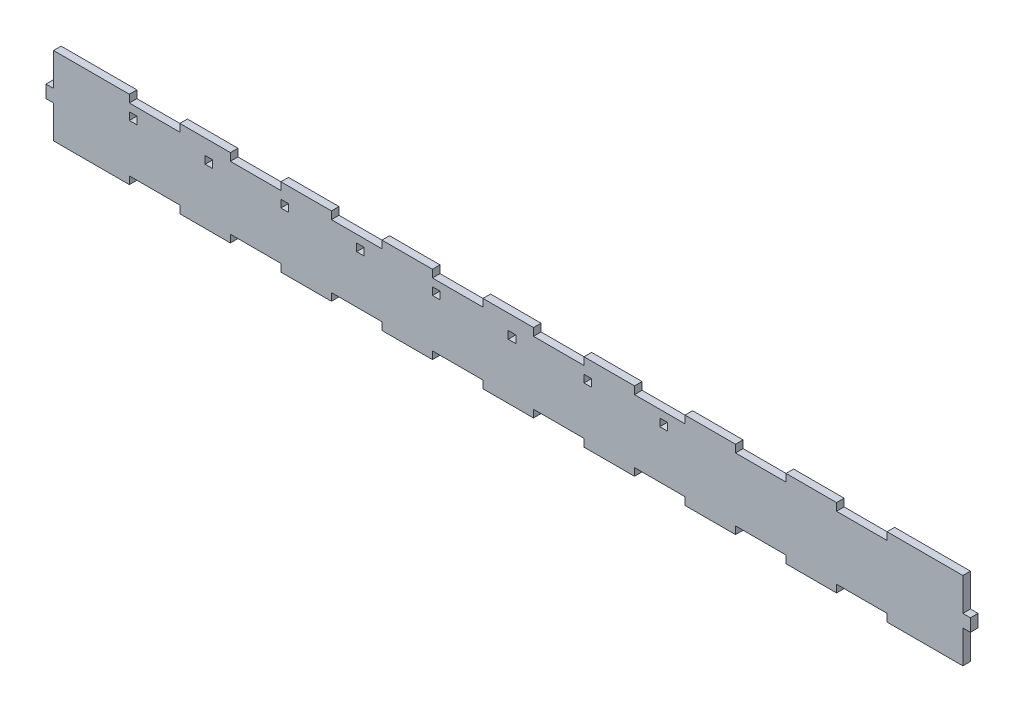
SolidWorks part; units mm, degrees
ref_plane "Front Plane" through (0, 0, 0) normal (0, 0, 1) x (1, 0, 0)
ref_plane "Top Plane" through (0, 0, 0) normal (0, 1, 0) x (1, 0, 0)
ref_plane "Right Plane" through (0, 0, 0) normal (1, 0, 0) x (0, 0, -1)
sketch "Эскиз1" plane through (0, 0, 0) normal (0, 0, 1) x (1, 0, 0)
  line L0 (193.8008, 182.8751) -> (201.5139, 182.8751)
  line L1 (201.5139, 182.8751) -> (201.5139, 187.2691)
  line L2 (201.5139, 187.2691) -> (225.208, 187.2691)
  line L3 (225.208, 187.2691) -> (225.208, 182.8751)
  line L4 (225.208, 182.8751) -> (247.3733, 182.8751)
  line L5 (247.3733, 182.8751) -> (247.3733, 187.2691)
  line L6 (247.3733, 187.2691) -> (271.0674, 187.2691)
  line L7 (271.0674, 187.2691) -> (271.0674, 182.8751)
  line L8 (271.0674, 182.8751) -> (301.6403, 182.8751)
  line L9 (301.6403, 182.8751) -> (301.6403, 159.44)
  line L10 (301.6403, 159.44) -> (307.3727, 159.44)
  line L11 (307.3727, 159.44) -> (307.3727, 141.2778)
  line L12 (307.3727, 141.2778) -> (301.6403, 141.2778)
  line L13 (301.6403, 141.2778) -> (301.6403, 124.2873)
  line L14 (301.6403, 124.2873) -> (307.3727, 124.2873)
  line L15 (307.3727, 124.2873) -> (307.3727, 106.1251)
  line L16 (307.3727, 106.1251) -> (301.6403, 106.1251)
  line L17 (301.6403, 106.1251) -> (301.6403, 89.1347)
  line L18 (301.6403, 89.1347) -> (307.3727, 89.1347)
  line L19 (307.3727, 89.1347) -> (307.3727, 70.9725)
  line L20 (307.3727, 70.9725) -> (301.6403, 70.9725)
  line L21 (301.6403, 70.9725) -> (301.6403, 53.9821)
  line L22 (301.6403, 53.9821) -> (307.3727, 53.9821)
  line L23 (307.3727, 53.9821) -> (307.3727, 35.8199)
  line L24 (307.3727, 35.8199) -> (301.6403, 35.8199)
  line L25 (301.6403, 35.8199) -> (301.6403, 18.8294)
  line L26 (301.6403, 18.8294) -> (307.3727, 18.8294)
  line L27 (307.3727, 18.8294) -> (307.3727, 0.6672)
  line L28 (307.3727, 0.6672) -> (301.6403, 0.6672)
  line L29 (301.6403, 0.6672) -> (301.6403, -16.3232)
  line L30 (301.6403, -16.3232) -> (307.3727, -16.3232)
  line L31 (307.3727, -16.3232) -> (307.3727, -34.4854)
  line L32 (307.3727, -34.4854) -> (301.6403, -34.4854)
  line L33 (301.6403, -67.207) -> (270.4792, -67.207)
  line L34 (270.4792, -67.207) -> (270.4792, -71.6011)
  line L35 (270.4792, -71.6011) -> (246.7851, -71.6011)
  line L36 (246.7851, -71.6011) -> (246.7851, -67.207)
  line L37 (246.7851, -67.207) -> (224.6198, -67.207)
  line L38 (224.6198, -67.207) -> (224.6198, -71.6011)
  line L39 (224.6198, -71.6011) -> (200.9257, -71.6011)
  line L40 (200.9257, -71.6011) -> (200.9257, -67.207)
  line L41 (200.9257, -67.207) -> (193.2126, -67.207)
  line L42 (193.2126, -67.207) -> (178.7604, -67.207)
  line L43 (178.7604, -67.207) -> (178.7604, -71.6011)
  line L44 (178.7604, -71.6011) -> (155.0663, -71.6011)
  line L45 (155.0663, -71.6011) -> (155.0663, -67.207)
  line L46 (155.0663, -67.207) -> (132.901, -67.207)
  line L47 (132.901, -67.207) -> (132.901, -71.6011)
  line L48 (132.901, -71.6011) -> (109.2069, -71.6011)
  line L49 (109.2069, -71.6011) -> (109.2069, -67.207)
  line L50 (109.2069, -67.207) -> (87.0415, -67.207)
  line L51 (87.0415, -67.207) -> (87.0415, -71.6011)
  line L52 (87.0415, -71.6011) -> (63.3475, -71.6011)
  line L53 (63.3475, -71.6011) -> (63.3475, -67.207)
  line L54 (63.3475, -67.207) -> (41.1821, -67.207)
  line L55 (41.1821, -67.207) -> (41.1821, -71.6011)
  line L56 (41.1821, -71.6011) -> (17.4881, -71.6011)
  line L57 (17.4881, -71.6011) -> (17.4881, -67.207)
  line L58 (17.4881, -67.207) -> (-4.6773, -67.207)
  line L59 (-4.6773, -67.207) -> (-4.6773, -71.6011)
  line L60 (-4.6773, -71.6011) -> (-28.3713, -71.6011)
  line L61 (-28.3713, -71.6011) -> (-28.3713, -67.207)
  line L62 (-28.3713, -67.207) -> (-58.356, -67.207)
  line L63 (-58.356, -67.207) -> (-58.356, -34.4854)
  line L64 (-58.356, -34.4854) -> (-64.0885, -34.4854)
  line L65 (-64.0885, -34.4854) -> (-64.0885, -16.3232)
  line L66 (-64.0885, -16.3232) -> (-58.356, -16.3232)
  line L67 (-58.356, -16.3232) -> (-58.356, 0.6672)
  line L68 (-58.356, 0.6672) -> (-64.0885, 0.6672)
  line L69 (-64.0885, 0.6672) -> (-64.0885, 18.8294)
  line L70 (-64.0885, 18.8294) -> (-58.356, 18.8294)
  line L71 (-58.356, 18.8294) -> (-58.356, 35.8199)
  line L72 (-58.356, 35.8199) -> (-64.0885, 35.8199)
  line L73 (-64.0885, 35.8199) -> (-64.0885, 53.9821)
  line L74 (-64.0885, 53.9821) -> (-58.356, 53.9821)
  line L75 (-58.356, 53.9821) -> (-58.356, 70.9725)
  line L76 (-58.356, 70.9725) -> (-64.0885, 70.9725)
  line L77 (-64.0885, 70.9725) -> (-64.0885, 89.1347)
  line L78 (-64.0885, 89.1347) -> (-58.356, 89.1347)
  line L79 (-58.356, 89.1347) -> (-58.356, 106.1251)
  line L80 (-58.356, 106.1251) -> (-64.0885, 106.1251)
  line L81 (-64.0885, 106.1251) -> (-64.0885, 124.2873)
  line L82 (-64.0885, 124.2873) -> (-58.356, 124.2873)
  line L83 (-58.356, 124.2873) -> (-58.356, 141.2778)
  line L84 (-58.356, 141.2778) -> (-64.0885, 141.2778)
  line L85 (-64.0885, 141.2778) -> (-64.0885, 159.44)
  line L86 (-64.0885, 159.44) -> (-58.356, 159.44)
  line L87 (-58.356, 159.44) -> (-58.356, 182.8751)
  line L88 (-58.356, 182.8751) -> (-27.7831, 182.8751)
  line L89 (-27.7831, 182.8751) -> (-27.7831, 187.2691)
  line L90 (-27.7831, 187.2691) -> (-4.0891, 187.2691)
  line L91 (-4.0891, 187.2691) -> (-4.0891, 182.8751)
  line L92 (-4.0891, 182.8751) -> (18.0763, 182.8751)
  line L93 (18.0763, 182.8751) -> (18.0763, 187.2691)
  line L94 (18.0763, 187.2691) -> (41.7703, 187.2691)
  line L95 (41.7703, 187.2691) -> (41.7703, 182.8751)
  line L96 (41.7703, 182.8751) -> (63.9357, 182.8751)
  line L97 (63.9357, 182.8751) -> (63.9357, 187.2691)
  line L98 (63.9357, 187.2691) -> (87.6297, 187.2691)
  line L99 (87.6297, 187.2691) -> (87.6297, 182.8751)
  line L100 (87.6297, 182.8751) -> (109.7951, 182.8751)
  line L101 (109.7951, 182.8751) -> (109.7951, 187.2691)
  line L102 (109.7951, 187.2691) -> (133.4892, 187.2691)
  line L103 (133.4892, 187.2691) -> (133.4892, 182.8751)
  line L104 (133.4892, 182.8751) -> (155.6545, 182.8751)
  line L105 (155.6545, 182.8751) -> (155.6545, 187.2691)
  line L106 (155.6545, 187.2691) -> (179.3486, 187.2691)
  line L107 (179.3486, 187.2691) -> (179.3486, 182.8751)
  line L108 (179.3486, 182.8751) -> (193.8008, 182.8751)
  line L109 (-61.3459, -78.4574) -> (-30.9012, -78.4574)
  line L110 (-30.9012, -78.4574) -> (-30.9012, -82.7686)
  line L111 (-30.9012, -82.7686) -> (-6.4981, -82.7686)
  line L112 (-6.4981, -82.7686) -> (-6.4981, -78.4574)
  line L113 (-6.4981, -78.4574) -> (14.958, -78.4574)
  line L114 (14.958, -78.4574) -> (14.958, -82.7686)
  line L115 (14.958, -82.7686) -> (39.3435, -82.7686)
  line L116 (39.3435, -82.7686) -> (39.3435, -78.4574)
  line L117 (39.3435, -78.4574) -> (60.7425, -78.4574)
  line L118 (60.7425, -78.4574) -> (60.7425, -82.7686)
  line L119 (60.7425, -82.7686) -> (85.2373, -82.7686)
  line L120 (85.2373, -82.7686) -> (85.2373, -78.4574)
  line L121 (85.2373, -78.4574) -> (106.671, -78.4574)
  line L122 (106.671, -78.4574) -> (106.671, -82.7686)
  line L123 (106.671, -82.7686) -> (131.0375, -82.7686)
  line L124 (131.0375, -82.7686) -> (131.0375, -78.4574)
  line L125 (131.0375, -78.4574) -> (152.4105, -78.4574)
  line L126 (152.4105, -78.4574) -> (152.4105, -82.7686)
  line L127 (152.4105, -82.7686) -> (176.9033, -82.7686)
  line L128 (176.9033, -82.7686) -> (176.9033, -78.4574)
  line L129 (176.9033, -78.4574) -> (198.3512, -78.4574)
  line L130 (198.3512, -78.4574) -> (198.3512, -82.7686)
  line L131 (198.3512, -82.7686) -> (222.7186, -82.7686)
  line L132 (222.7186, -82.7686) -> (222.7186, -78.4574)
  line L133 (222.7186, -78.4574) -> (244.191, -78.4574)
  line L134 (244.191, -78.4574) -> (244.191, -82.7686)
  line L135 (244.191, -82.7686) -> (268.7496, -82.7686)
  line L136 (268.7496, -82.7686) -> (268.7496, -78.4574)
  line L137 (268.7496, -78.4574) -> (299.0743, -78.4574)
  line L138 (299.0743, -78.4574) -> (299.0743, -90.1442)
  line L139 (299.0743, -90.1442) -> (307.1171, -90.1442)
  line L140 (307.1171, -90.1442) -> (307.1106, -97.0135)
  line L141 (307.1106, -97.0135) -> (299.0743, -97.0135)
  line L142 (299.0743, -97.0135) -> (299.0743, -109.9393)
  line L143 (299.0743, -109.9393) -> (268.7496, -109.9393)
  line L144 (268.7496, -109.9393) -> (268.7496, -106.2126)
  line L145 (268.7496, -106.2126) -> (244.191, -106.2126)
  line L146 (244.191, -106.2126) -> (244.191, -109.9393)
  line L147 (244.191, -109.9393) -> (222.7186, -109.9393)
  line L148 (222.7186, -109.9393) -> (222.7186, -106.2126)
  line L149 (222.7186, -106.2126) -> (198.3512, -106.2126)
  line L150 (198.3512, -106.2126) -> (198.3512, -109.9393)
  line L151 (198.3512, -109.9393) -> (176.9033, -109.9393)
  line L152 (176.9033, -109.9393) -> (176.9033, -106.2126)
  line L153 (176.9033, -106.2126) -> (152.4105, -106.2126)
  line L154 (152.4105, -106.2126) -> (152.4105, -109.9393)
  line L155 (152.4105, -109.9393) -> (131.0375, -109.9393)
  line L156 (131.0375, -109.9393) -> (131.0369, -106.2126)
  line L157 (131.0369, -106.2126) -> (106.671, -106.2126)
  line L158 (106.671, -106.2126) -> (106.671, -109.9393)
  line L159 (106.671, -109.9393) -> (85.2373, -109.9393)
  line L160 (85.2373, -109.9393) -> (85.2373, -106.2126)
  line L161 (85.2373, -106.2126) -> (60.7425, -106.2126)
  line L162 (60.7425, -106.2126) -> (60.7425, -109.9393)
  line L163 (60.7425, -109.9393) -> (39.3435, -109.9393)
  line L164 (39.3435, -109.9393) -> (39.3435, -106.2126)
  line L165 (39.3435, -106.2126) -> (14.958, -106.2126)
  line L166 (14.958, -106.2126) -> (14.958, -109.9393)
  line L167 (14.958, -109.9393) -> (-6.4981, -109.9393)
  line L168 (-6.4981, -109.9393) -> (-6.4981, -106.2126)
  line L169 (-6.4981, -106.2126) -> (-30.9012, -106.2126)
  line L170 (-30.9012, -106.2126) -> (-30.9012, -109.9393)
  line L171 (-30.9012, -109.9393) -> (-61.3459, -109.9393)
  line L172 (-61.3459, -109.9393) -> (-61.3459, -97.2134)
  line L173 (-61.3459, -97.2134) -> (-68.0491, -97.2134)
  line L174 (-68.0491, -97.2134) -> (-68.0491, -90.3441)
  line L175 (-68.0491, -90.3441) -> (-61.3459, -90.3441)
  line L176 (-61.3459, -90.3441) -> (-61.3459, -78.4574)
  line L177 (2.2288, -97.5594) -> (2.2288, -90.303)
  line L178 (2.2288, -90.303) -> (5.0674, -90.303)
  line L179 (5.0674, -90.303) -> (5.0674, -97.5594)
  line L180 (5.0674, -97.5594) -> (2.2288, -97.5594)
  line L181 (-27.781, -97.5195) -> (-27.781, -90.2855)
  line L182 (-27.781, -90.2855) -> (-24.9424, -90.2855)
  line L183 (-24.9424, -90.2855) -> (-24.9424, -97.5195)
  line L184 (-24.9424, -97.5195) -> (-27.781, -97.5195)
  line L185 (32.2346, -97.5095) -> (32.2346, -90.2755)
  line L186 (32.2346, -90.2755) -> (35.0732, -90.2755)
  line L187 (35.0732, -90.2755) -> (35.0732, -97.5095)
  line L188 (35.0732, -97.5095) -> (32.2346, -97.5095)
  line L189 (62.2324, -97.5056) -> (62.2324, -90.293)
  line L190 (62.2324, -90.293) -> (65.071, -90.293)
  line L191 (65.071, -90.293) -> (65.071, -97.5056)
  line L192 (65.071, -97.5056) -> (62.2324, -97.5056)
  line L193 (122.2524, -97.3934) -> (122.2524, -90.2855)
  line L194 (122.2524, -90.2855) -> (125.091, -90.2855)
  line L195 (125.091, -90.2855) -> (125.091, -97.3934)
  line L196 (125.091, -97.3934) -> (122.2524, -97.3934)
  line L197 (95.0743, -90.2854) -> (95.0743, -94.4236)
  line L198 (95.0743, -94.4236) -> (95.0743, -97.4585)
  line L199 (95.0743, -97.4585) -> (92.2357, -97.4585)
  line L200 (92.2357, -97.4585) -> (92.2357, -90.2854)
  line L201 (92.2357, -90.2854) -> (95.0743, -90.2854)
  line L202 (152.2582, -97.2561) -> (152.2582, -90.2855)
  line L203 (152.2582, -90.2855) -> (155.0968, -90.2855)
  line L204 (155.0968, -90.2855) -> (155.0968, -97.2561)
  line L205 (155.0968, -97.2561) -> (152.2582, -97.2561)
  line L206 (185.8545, -97.2723) -> (185.8545, -90.2764)
  line L207 (185.8545, -90.2764) -> (188.7034, -90.2764)
  line L208 (188.7034, -90.2764) -> (188.7034, -97.2723)
  line L209 (188.7034, -97.2723) -> (185.8545, -97.2723)
  line L210 (343.9726, 175.5495) -> (343.9726, 144.6496)
  line L211 (343.9726, 144.6496) -> (338.0857, 144.6496)
  line L212 (338.0857, 144.6496) -> (338.0857, 126.0874)
  line L213 (338.0857, 126.0874) -> (343.9726, 126.0874)
  line L214 (343.9726, 126.0874) -> (343.9726, 109.4969)
  line L215 (343.9726, 109.4969) -> (338.0857, 109.4969)
  line L216 (338.0857, 109.4969) -> (338.0857, 90.7435)
  line L217 (338.0857, 90.7435) -> (343.9726, 90.7435)
  line L218 (343.9726, 90.7435) -> (343.9726, 74.3443)
  line L219 (343.9726, 74.3443) -> (338.0857, 74.3443)
  line L220 (338.0857, 74.3443) -> (338.0857, 55.9821)
  line L221 (338.0857, 55.9821) -> (343.9726, 55.9821)
  line L222 (343.9726, 55.9821) -> (343.9726, 39.1917)
  line L223 (343.9726, 39.1917) -> (338.0857, 39.1917)
  line L224 (338.0857, 39.1917) -> (338.0857, 20.6295)
  line L225 (338.0857, 20.6295) -> (343.9726, 20.6295)
  line L226 (343.9726, 20.6295) -> (343.9726, 4.039)
  line L227 (343.9726, 4.039) -> (338.0857, 4.039)
  line L228 (338.0857, 4.039) -> (338.0857, -14.3232)
  line L229 (338.0857, -14.3232) -> (343.9726, -14.3232)
  line L230 (343.9726, -14.3232) -> (343.9726, -31.3136)
  line L231 (343.9726, -31.3136) -> (338.0857, -31.3136)
  line L232 (338.0857, -31.3136) -> (338.0857, -49.4758)
  line L233 (338.0857, -49.4758) -> (343.9726, -49.4758)
  line L234 (343.9726, -49.4758) -> (343.9726, -58.8018)
  line L235 (343.9726, -58.8018) -> (343.9726, -89.4934)
  line L236 (343.9726, -89.4934) -> (331.9328, -89.4934)
  line L237 (331.9328, -89.4934) -> (331.9328, -82.0768)
  line L238 (331.9328, -82.0768) -> (324.634, -82.0768)
  line L239 (324.634, -82.0768) -> (324.634, -89.4934)
  line L240 (324.634, -89.4934) -> (311.9156, -89.4934)
  line L241 (311.9156, -49.4758) -> (318.2807, -49.4758)
  line L242 (318.2807, -49.4758) -> (318.2807, -31.3136)
  line L243 (318.2807, -31.3136) -> (311.9156, -31.3136)
  line L244 (311.9156, -31.3136) -> (311.9156, -14.3232)
  line L245 (311.9156, -14.3232) -> (318.2807, -14.3232)
  line L246 (318.2807, -14.3232) -> (318.2807, 4.039)
  line L247 (318.2807, 4.039) -> (311.9156, 4.039)
  line L248 (311.9156, 4.039) -> (311.9156, 20.6295)
  line L249 (311.9156, 20.6295) -> (318.2807, 20.6295)
  line L250 (318.2807, 20.6295) -> (318.2807, 39.1917)
  line L251 (318.2807, 39.1917) -> (311.9156, 39.1917)
  line L252 (311.9156, 39.1917) -> (311.9156, 55.9821)
  line L253 (311.9156, 55.9821) -> (318.2807, 55.9821)
  line L254 (318.2807, 55.9821) -> (318.2807, 74.3443)
  line L255 (318.2807, 74.3443) -> (311.9156, 74.3443)
  line L256 (311.9156, 74.3443) -> (311.9156, 90.7435)
  line L257 (311.9156, 90.7435) -> (318.2807, 90.7435)
  line L258 (318.2807, 90.7435) -> (318.2807, 109.4969)
  line L259 (318.2807, 109.4969) -> (311.9156, 109.4969)
  line L260 (311.9156, 109.4969) -> (311.9156, 126.0874)
  line L261 (311.9156, 126.0874) -> (318.2807, 126.0874)
  line L262 (318.2807, 126.0874) -> (318.2807, 144.6496)
  line L263 (318.2807, 144.6496) -> (311.9156, 144.6496)
  line L264 (311.9156, 144.6496) -> (311.9156, 175.5495)
  line L265 (311.9156, 175.5495) -> (324.9437, 175.5495)
  line L266 (324.9437, 175.5495) -> (324.9437, 167.9766)
  line L267 (324.9437, 167.9766) -> (331.8631, 167.9766)
  line L268 (331.8631, 167.9766) -> (331.8631, 175.5495)
  line L269 (331.8631, 175.5495) -> (343.9726, 175.5495)
  line L270 (324.5991, 104.3627) -> (331.8555, 104.3627)
  line L271 (331.8555, 104.3627) -> (331.8555, 101.5241)
  line L272 (331.8555, 101.5241) -> (324.5991, 101.5241)
  line L273 (324.5991, 101.5241) -> (324.5991, 104.3627)
  line L274 (324.639, 134.3725) -> (331.873, 134.3725)
  line L275 (331.873, 134.3725) -> (331.873, 131.5339)
  line L276 (331.873, 131.5339) -> (324.639, 131.5339)
  line L277 (324.639, 131.5339) -> (324.639, 134.3725)
  line L278 (324.649, 74.3569) -> (331.883, 74.3569)
  line L279 (331.883, 74.3569) -> (331.883, 71.5183)
  line L280 (331.883, 71.5183) -> (324.649, 71.5183)
  line L281 (324.649, 71.5183) -> (324.649, 74.3569)
  line L282 (324.6529, 44.3591) -> (331.8655, 44.3591)
  line L283 (331.8655, 44.3591) -> (331.8655, 41.5205)
  line L284 (331.8655, 41.5205) -> (324.6529, 41.5205)
  line L285 (324.6529, 41.5205) -> (324.6529, 44.3591)
  line L286 (324.7651, -15.6609) -> (331.873, -15.6609)
  line L287 (331.873, -15.6609) -> (331.873, -18.4995)
  line L288 (331.873, -18.4995) -> (324.7651, -18.4995)
  line L289 (324.7651, -18.4995) -> (324.7651, -15.6609)
  line L290 (331.8731, 11.5172) -> (327.7349, 11.5172)
  line L291 (327.7349, 11.5172) -> (324.7, 11.5172)
  line L292 (324.7, 11.5172) -> (324.7, 14.3558)
  line L293 (324.7, 14.3558) -> (331.8731, 14.3558)
  line L294 (331.8731, 14.3558) -> (331.8731, 11.5172)
  line L295 (324.9024, -45.6667) -> (331.873, -45.6667)
  line L296 (331.873, -45.6667) -> (331.873, -48.5053)
  line L297 (331.873, -48.5053) -> (324.9024, -48.5053)
  line L298 (324.9024, -48.5053) -> (324.9024, -45.6667)
  spline S0 degree 3 poles (301.6403, -34.4854) (301.6403, -60.9873) (301.6403, -37.2965) (301.6403, -67.207) knots 0.3 0.3 0.3 0.3 0.309091 0.309091 0.309091 0.309091
  spline S1 degree 3 poles (311.9156, -89.4934) (311.9156, -76.1542) (311.9156, -62.815) (311.9156, -49.4758) knots 0.508197 0.508197 0.508197 0.508197 0.52459 0.52459 0.52459 0.52459
sketch "Sketch1" plane through (0, 0, 0) normal (0, 0, 1) x (1, 0, 0)
  line L0 (28.4429, -76.8527) -> (28.4429, -79.8527)
  line L1 (-31.5571, -79.8527) -> (-11.5571, -79.8527)
  line L2 (-61.5571, -79.8527) -> (-61.5571, -89.8527)
  line L3 (-31.5571, -104.8527) -> (-11.5571, -104.8527)
  line L4 (298.4429, -79.8527) -> (298.4429, -89.8527)
  line L6 (-61.5571, -79.8527) -> (-61.5571, -76.8527)
  line L7 (-61.5571, -76.8527) -> (-31.5571, -76.8527)
  line L8 (-31.5571, -79.8527) -> (-31.5571, -76.8527)
  line L9 (-61.5571, -89.8527) -> (-64.5571, -89.8527)
  line L11 (-61.5571, -94.8527) -> (-64.5571, -94.8527)
  line L12 (-64.5571, -89.8527) -> (-64.5571, -94.8527)
  line L13 (-11.5571, -76.8527) -> (8.4429, -76.8527)
  line L14 (-11.5571, -76.8527) -> (-11.5571, -79.8527)
  line L16 (8.4429, -76.8527) -> (8.4429, -79.8527)
  line L17 (28.4429, -76.8527) -> (48.4429, -76.8527)
  line L18 (48.4429, -76.8527) -> (48.4429, -79.8527)
  line L20 (68.4429, -76.8527) -> (68.4429, -79.8527)
  line L21 (68.4429, -76.8527) -> (88.4429, -76.8527)
  line L22 (88.4429, -76.8527) -> (88.4429, -79.8527)
  line L24 (108.4429, -76.8527) -> (108.4429, -79.8527)
  line L25 (108.4429, -76.8527) -> (128.4429, -76.8527)
  line L26 (128.4429, -76.8527) -> (128.4429, -79.8527)
  line L28 (148.4429, -76.8527) -> (148.4429, -79.8527)
  line L29 (148.4429, -76.8527) -> (168.4429, -76.8527)
  line L30 (168.4429, -76.8527) -> (168.4429, -79.8527)
  line L32 (188.4429, -76.8527) -> (188.4429, -79.8527)
  line L33 (188.4429, -76.8527) -> (208.4429, -76.8527)
  line L34 (208.4429, -76.8527) -> (208.4429, -79.8527)
  line L36 (228.4429, -76.8527) -> (228.4429, -79.8527)
  line L37 (228.4429, -76.8527) -> (248.4429, -76.8527)
  line L38 (248.4429, -76.8527) -> (248.4429, -79.8527)
  line L40 (118.4429, -104.8527) -> (118.4429, -89.8527) construction
  line L41 (-61.5571, -94.8527) -> (-61.5571, -104.8527)
  line L42 (298.4429, -94.8527) -> (301.4429, -94.8527)
  line L43 (301.4429, -89.8527) -> (301.4429, -94.8527)
  line L44 (298.4429, -89.8527) -> (301.4429, -89.8527)
  line L46 (298.4429, -76.8527) -> (268.4429, -76.8527)
  line L47 (268.4429, -79.8527) -> (268.4429, -76.8527)
  line L49 (298.4429, -79.8527) -> (298.4429, -76.8527)
  line L50 (298.4429, -92.3527) -> (255.9136, -92.3527) construction
  line L52 (268.4429, -104.8527) -> (268.4429, -107.8527)
  line L53 (298.4429, -107.8527) -> (268.4429, -107.8527)
  line L54 (298.4429, -104.8527) -> (298.4429, -107.8527)
  line L55 (228.4429, -107.8527) -> (248.4429, -107.8527)
  line L56 (248.4429, -107.8527) -> (248.4429, -104.8527)
  line L58 (228.4429, -107.8527) -> (228.4429, -104.8527)
  line L59 (188.4429, -107.8527) -> (208.4429, -107.8527)
  line L60 (208.4429, -107.8527) -> (208.4429, -104.8527)
  line L62 (188.4429, -107.8527) -> (188.4429, -104.8527)
  line L63 (148.4429, -107.8527) -> (168.4429, -107.8527)
  line L64 (168.4429, -107.8527) -> (168.4429, -104.8527)
  line L66 (148.4429, -107.8527) -> (148.4429, -104.8527)
  line L67 (108.4429, -107.8527) -> (128.4429, -107.8527)
  line L68 (128.4429, -107.8527) -> (128.4429, -104.8527)
  line L70 (108.4429, -107.8527) -> (108.4429, -104.8527)
  line L71 (68.4429, -107.8527) -> (88.4429, -107.8527)
  line L72 (88.4429, -107.8527) -> (88.4429, -104.8527)
  line L74 (68.4429, -107.8527) -> (68.4429, -104.8527)
  line L75 (28.4429, -107.8527) -> (48.4429, -107.8527)
  line L76 (48.4429, -107.8527) -> (48.4429, -104.8527)
  line L78 (28.4429, -107.8527) -> (28.4429, -104.8527)
  line L80 (8.4429, -107.8527) -> (8.4429, -104.8527)
  line L81 (-11.5571, -107.8527) -> (8.4429, -107.8527)
  line L82 (-11.5571, -107.8527) -> (-11.5571, -104.8527)
  line L83 (-61.5571, -107.8527) -> (-31.5571, -107.8527)
  line L84 (-31.5571, -104.8527) -> (-31.5571, -107.8527)
  line L86 (-61.5571, -104.8527) -> (-61.5571, -107.8527)
  line L87 (8.4429, -104.8527) -> (28.4429, -104.8527)
  line L88 (8.4429, -79.8527) -> (28.4429, -79.8527)
  line L89 (48.4429, -79.8527) -> (68.4429, -79.8527)
  line L90 (48.4429, -104.8527) -> (68.4429, -104.8527)
  line L91 (88.4429, -79.8527) -> (108.4429, -79.8527)
  line L92 (88.4429, -104.8527) -> (108.4429, -104.8527)
  line L93 (128.4429, -79.8527) -> (148.4429, -79.8527)
  line L94 (128.4429, -104.8527) -> (148.4429, -104.8527)
  line L95 (168.4429, -104.8527) -> (188.4429, -104.8527)
  line L96 (168.4429, -79.8527) -> (188.4429, -79.8527)
  line L97 (208.4429, -79.8527) -> (228.4429, -79.8527)
  line L98 (208.4429, -104.8527) -> (228.4429, -104.8527)
  line L99 (248.4429, -79.8527) -> (268.4429, -79.8527)
  line L100 (248.4429, -104.8527) -> (268.4429, -104.8527)
  line L101 (298.4429, -94.8527) -> (298.4429, -104.8527)
  line L102 (-1.5571, -82.8527) -> (-1.5571, -85.8527)
  line L103 (-31.5571, -82.8527) -> (-28.5571, -82.8527)
  line L104 (-31.5571, -82.8527) -> (-31.5571, -85.8527)
  line L105 (-31.5571, -85.8527) -> (-28.5571, -85.8527)
  line L106 (-28.5571, -82.8527) -> (-28.5571, -85.8527)
  line L107 (-1.5571, -82.8527) -> (1.4429, -82.8527)
  line L108 (1.4429, -82.8527) -> (1.4429, -85.8527)
  line L109 (-1.5571, -85.8527) -> (1.4429, -85.8527)
  line L110 (28.4429, -82.8527) -> (28.4429, -85.8527)
  line L111 (28.4429, -82.8527) -> (31.4429, -82.8527)
  line L112 (31.4429, -82.8527) -> (31.4429, -85.8527)
  line L113 (28.4429, -85.8527) -> (31.4429, -85.8527)
  line L114 (58.4429, -82.8527) -> (58.4429, -85.8527)
  line L115 (58.4429, -82.8527) -> (61.4429, -82.8527)
  line L116 (61.4429, -82.8527) -> (61.4429, -85.8527)
  line L117 (58.4429, -85.8527) -> (61.4429, -85.8527)
  line L118 (88.4429, -82.8527) -> (88.4429, -85.8527)
  line L119 (88.4429, -82.8527) -> (91.4429, -82.8527)
  line L120 (91.4429, -82.8527) -> (91.4429, -85.8527)
  line L121 (88.4429, -85.8527) -> (91.4429, -85.8527)
  line L122 (118.4429, -82.8527) -> (118.4429, -85.8527)
  line L123 (118.4429, -82.8527) -> (121.4429, -82.8527)
  line L124 (121.4429, -82.8527) -> (121.4429, -85.8527)
  line L125 (118.4429, -85.8527) -> (121.4429, -85.8527)
  line L126 (148.4429, -82.8527) -> (148.4429, -85.8527)
  line L127 (148.4429, -82.8527) -> (151.4429, -82.8527)
  line L128 (151.4429, -82.8527) -> (151.4429, -85.8527)
  line L129 (148.4429, -85.8527) -> (151.4429, -85.8527)
  line L130 (178.4429, -82.8527) -> (178.4429, -85.8527)
  line L131 (178.4429, -82.8527) -> (181.4429, -82.8527)
  line L132 (181.4429, -82.8527) -> (181.4429, -85.8527)
  line L133 (178.4429, -85.8527) -> (181.4429, -85.8527)
  point P88 (0, 0)
  dimension "D1" = 25
  dimension "D2" = 360
  dimension "D3" = 3
  dimension "D4" = 30
  dimension "D5" = 3
  dimension "D6" = 5
  dimension "D7" = 10
  dimension "D8" = 20
  dimension "D9" = 20
  dimension "D11" = 20
  dimension "D12" = 3
  dimension "D13" = 3
  dimension "D14" = 3
  dimension "D15" = 3
  dimension "D16" = 30
  dimension "D18" = 27
  dimension "D19" = 3
  dimension "D10" = 7
  dimension "D17" = 8
extrude "Boss-Extrude2" add sketch "Sketch1" along normal blind 3
